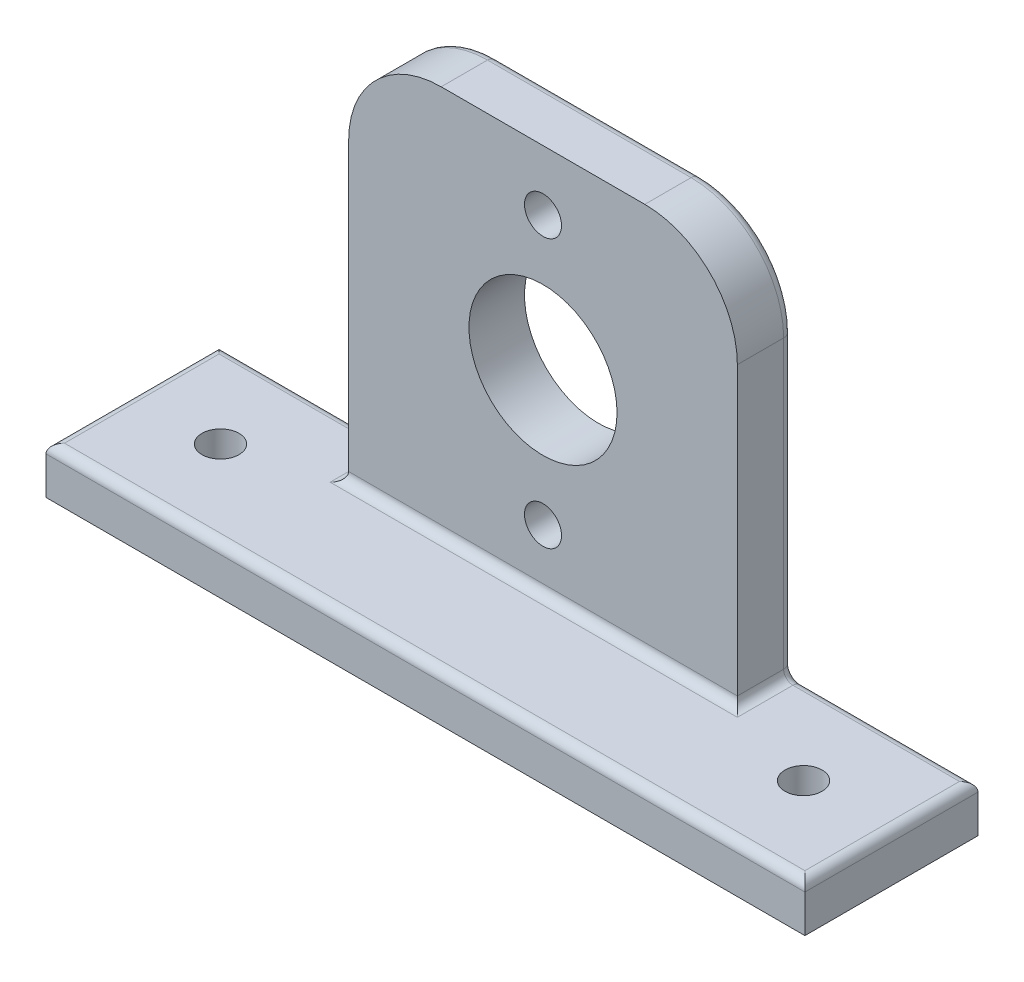
SolidWorks part; units mm, degrees
ref_plane "Front Plane" through (0, 0, 0) normal (0, 0, 1) x (1, 0, 0)
ref_plane "Top Plane" through (0, 0, 0) normal (0, 1, 0) x (1, 0, 0)
ref_plane "Right Plane" through (0, 0, 0) normal (1, 0, 0) x (0, 0, -1)
sketch "Sketch1" plane through (0, 0, 0) normal (0, 0, 1) x (1, 0, 0)
  line L0 (0, 0) -> (82, 0)
  line L1 (82, 0) -> (82, 5.08)
  line L2 (82, 5.08) -> (62, 5.08)
  line L3 (0, 0) -> (0, 5.08)
  line L4 (0, 5.08) -> (20, 5.08)
  line L5 (20, 5.08) -> (20, 47.08)
  line L6 (20, 47.08) -> (62, 47.08)
  line L7 (62, 47.08) -> (62, 5.08)
  line L10 (-19.4755, 26.08) -> (92.5505, 26.08) construction
  line L11 (41, 58.4606) -> (41, -15.2115) construction
  circle A0 centre (41, 40.58) radius 2
  circle A1 centre (41, 11.58) radius 2
  circle A2 centre (41, 26.08) radius 8
  dimension "D8" = 14.5
  dimension "D10" = 4
  dimension "D11" = 4
  dimension "D12" = 16
  dimension "D1" = 42
  dimension "D2" = 20
  dimension "D3" = 20
  dimension "D4" = 42
  dimension "D5" = 5.08
  dimension "D6" = 21
  dimension "D7" = 21
  dimension "D9" = 14.5
extrude "Boss-Extrude1" add sketch "Sketch1" along normal blind 6
sketch "Sketch2" plane through (0, 0, 0) normal (1, 0, 0) x (0, 0, -1)
  line L0 (-6, 5.08) -> (0, 5.08) construction
  line L1 (-6, 0) -> (-18.7, 0)
  line L2 (-6, 0) -> (-6, 5.08)
  line L3 (-6, 5.08) -> (-18.7, 5.08)
  line L4 (-18.7, 0) -> (-18.7, 5.08)
  dimension "D1" = 12.7
extrude "Boss-Extrude2" add sketch "Sketch2" along normal through all
fillet "Fillet1" radius 10 1 edges at (20, 47.08, 3)
fillet "Fillet2" radius 10 1 edges at (62, 47.08, 3)
fillet "Fillet4" radius 1 13 edges at (41, 47.08, 0) (22.9289, 44.1511, 0) (59.0711, 44.1511, 0) (20, 21.08, 0) (62, 21.08, 0) (20, 5.08, 3) (41, 5.08, 6) (62, 5.08, 3) (72, 5.08, 0) (82, 5.08, 9.35) (41, 5.08, 18.7) (0, 5.08, 9.35) (10, 5.08, 0)
sketch "Sketch3" plane through (0, 0, 0) normal (0, 1, 0) x (1, 0, 0)
  line L0 (9.5, 11.2289) -> (9.5, -43.9468) construction
  line L1 (72.5, 11.2289) -> (72.5, -43.9468) construction
  line L2 (0, -18.7) -> (0, 0) construction
  line L3 (19, -7) -> (19, -1) construction
  line L4 (82, 0) -> (82, -18.7) construction
  line L5 (63, -1) -> (63, -7) construction
  line L6 (-7.241, -9.35) -> (96.846, -9.35) construction
  line L7 (0, 0) -> (19, 0) construction
  line L8 (82, -18.7) -> (0, -18.7) construction
  circle A0 centre (9.5, -9.35) radius 2
  circle A1 centre (72.5, -9.35) radius 2
  dimension "D1" = 4
  dimension "D2" = 4
extrude "Cut-Extrude1" cut sketch "Sketch3" along normal blind 6
